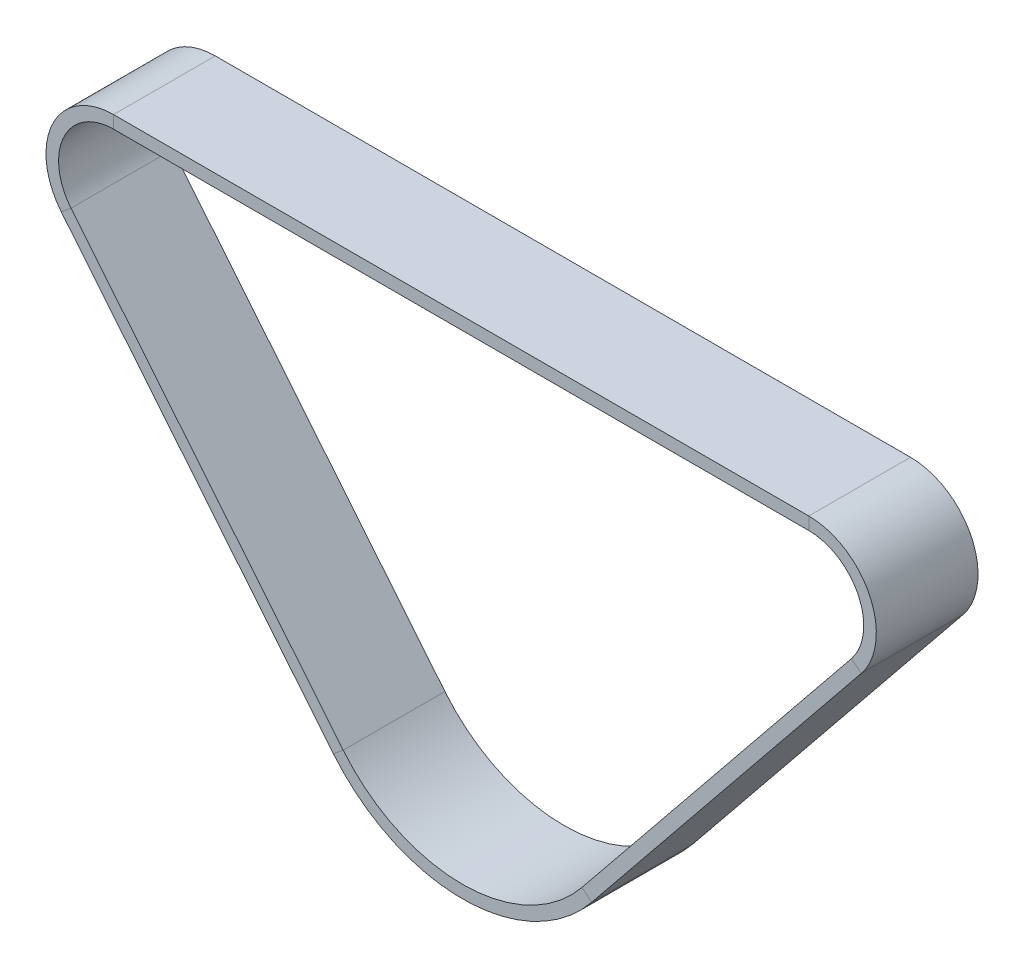
SolidWorks part; units mm, degrees
ref_plane "Front Plane" through (0, 0, 0) normal (0, 0, 1) x (1, 0, 0)
ref_plane "Top Plane" through (0, 0, 0) normal (0, 1, 0) x (1, 0, 0)
ref_plane "Right Plane" through (0, 0, 0) normal (1, 0, 0) x (0, 0, -1)
sketch "Sketch2" plane through (0, 0, 0) normal (0, 0, 1) x (1, 0, 0)
  line L0 (0, 0) -> (1, 0) construction
  line L1 (0, 0) -> (0, 1) construction
  line L2 (0, 7.65) -> (86.8218, 7.65)
  line L3 (92.7677, -4.8134) -> (59.1057, -46.3949)
  line L4 (28.0709, -46.4623) -> (-5.9249, -4.8392)
  arc A0 (-5.9249, -4.8392) -> (0, 7.65) centre (0, 0) cw
  arc A1 (86.8218, 7.65) -> (92.7677, -4.8134) centre (86.8218, 0) cw
  arc A2 (59.1057, -46.3949) -> (28.0709, -46.4623) centre (43.5609, -33.8108) cw
ref_plane "Plane1" through (0, 0, 0) normal (1, 0, 0) x (0, 0, -1)
sketch "Sketch3" plane through (0, 0, 0) normal (1, 0, 0) x (0, 0, -1)
  line L0 (0, 7.65) -> (0, -4.8134) construction
  line L1 (-6.35, 8.4374) -> (6.35, 8.4374)
  line L2 (-6.35, 8.4374) -> (-6.35, 6.8626)
  line L3 (-6.35, 6.8626) -> (6.35, 6.8626)
  line L4 (6.35, 8.4374) -> (6.35, 6.8626)
  line L5 (-6.35, 8.4374) -> (6.35, 6.8626) construction
  line L6 (-6.35, 6.8626) -> (6.35, 8.4374) construction
  line L7 (0, 7.65) -> (0, -4.8392) construction
  point P0 (0, 7.65)
  dimension "D1" = 12.7
  dimension "D2" = 1.5748
  dimension "D3" = 0
sweep "Sweep1" add profiles "Sketch3" path "Sketch2"
